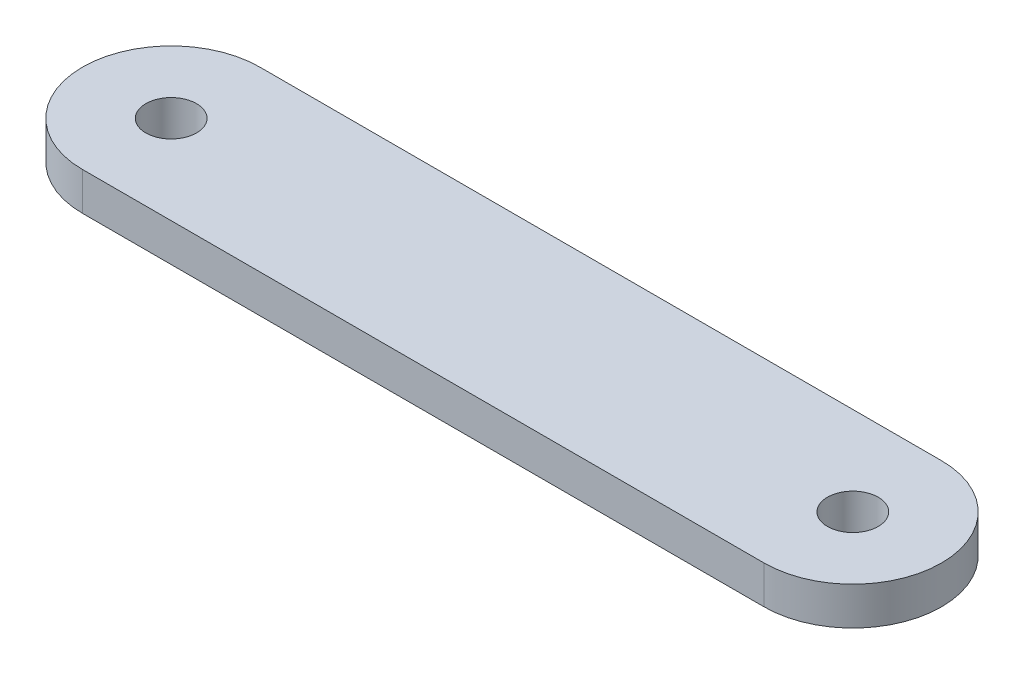
SolidWorks part; units mm, degrees
ref_plane "Front Plane" through (0, 0, 0) normal (0, 0, 1) x (1, 0, 0)
ref_plane "Top Plane" through (0, 0, 0) normal (0, 1, 0) x (1, 0, 0)
ref_plane "Right Plane" through (0, 0, 0) normal (1, 0, 0) x (0, 0, -1)
sketch "Sketch1" plane through (0, 0, 0) normal (0, 1, 0) x (1, 0, 0)
  line L0 (-26.905, 0) -> (26.905, 0) construction
  line L1 (-26.905, 7) -> (26.905, 7)
  line L2 (-26.905, -7) -> (26.905, -7)
  arc A0 (-26.905, 7) -> (-26.905, -7) centre (-26.905, 0) ccw
  arc A1 (26.905, -7) -> (26.905, 7) centre (26.905, 0) ccw
  circle A2 centre (-26.905, 0) radius 2.005
  circle A3 centre (26.905, 0) radius 2.005
  point P3 (0, 0)
  dimension "D2" = 7
  dimension "D3" = 4.01
  dimension "D4" = 4.01
  dimension "D1" = 53.81
  dimension "D5" = 53.81
extrude "Boss-Extrude1" add sketch "Sketch1" along normal blind 3
